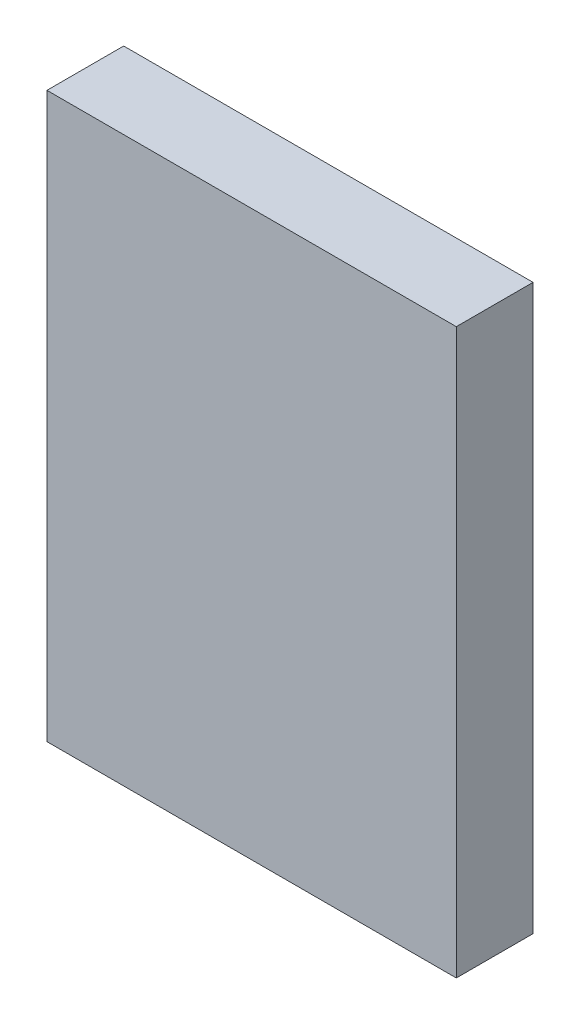
SolidWorks part; units mm, degrees
ref_plane "Alzado" through (0, 0, 0) normal (0, 0, 1) x (1, 0, 0)
ref_plane "Planta" through (0, 0, 0) normal (0, 1, 0) x (1, 0, 0)
ref_plane "Vista lateral" through (0, 0, 0) normal (1, 0, 0) x (0, 0, -1)
sketch "Croquis1" plane through (0, 0, 0) normal (0, 0, 1) x (1, 0, 0)
  line L1 (25.4, -35) -> (-25.4, -35)
  line L2 (25.4, -35) -> (25.4, 35)
  line L3 (25.4, 35) -> (-25.4, 35)
  line L4 (-25.4, -35) -> (-25.4, 35)
  line L5 (25.4, -35) -> (-25.4, 35) construction
  line L6 (25.4, 35) -> (-25.4, -35) construction
  point P0 (0, 0)
  dimension "D1" = 50.8
  dimension "D2" = 70
extrude "Saliente-Extruir1" add sketch "Croquis1" along normal blind 9.525
